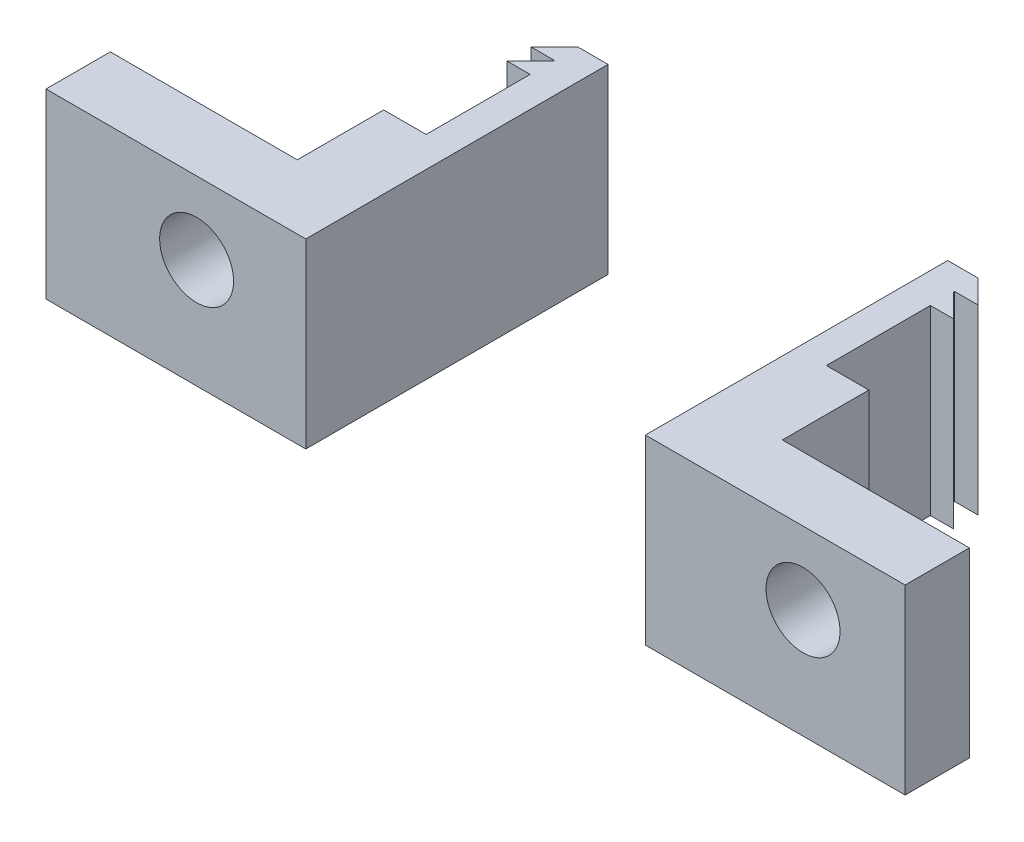
SolidWorks part; units mm, degrees
ref_plane "Front Plane" through (0, 0, 0) normal (0, 0, 1) x (1, 0, 0)
ref_plane "Top Plane" through (0, 0, 0) normal (0, 1, 0) x (1, 0, 0)
ref_plane "Right Plane" through (0, 0, 0) normal (1, 0, 0) x (0, 0, -1)
sketch "Sketch2" plane through (0, 0, 0) normal (0, 1, 0) x (1, 0, 0)
  line L0 (-13.5, 0) -> (6.5, 0)
  line L5 (11.5, -5) -> (11.5, -41)
  line L6 (11.5, -41) -> (31.9173, -41)
  line L7 (31.9173, -41) -> (31.9173, -35.699)
  line L8 (31.9173, -35.699) -> (16.5, -35.699)
  line L9 (16.5, -35.699) -> (16.5, 5)
  line L10 (16.5, 5) -> (-23.5, 5)
  line L11 (-23.5, 5) -> (-23.5, -35.699)
  line L12 (-23.5, -35.699) -> (-38.9173, -35.699)
  line L13 (-38.9173, -35.699) -> (-38.9173, -41)
  line L14 (-38.9173, -41) -> (-18.5, -41)
  line L15 (-18.5, -41) -> (-18.5, -5)
  line L16 (-23.5, -35.699) -> (-23.5, -53.6584) construction
  line L17 (-29.5, -29.038) -> (-29.5, -53.6584) construction
  line L18 (-29.5, -47.6505) -> (-23.5, -47.6505) construction
  line L19 (-3.5, 0) -> (-3.5, -26.0929) construction
  line L20 (-26.5, -47.6505) -> (-26.5, -68.2741) construction
  line L21 (23.5, -24.9282) -> (23.5, -62.6056) construction
  line L22 (20.5, -24.4655) -> (20.5, -49.1581) construction
  line L23 (26.5, -24.4655) -> (26.5, -49.1581) construction
  line L24 (20.5, -44.8687) -> (26.5, -44.8687) construction
  line L25 (23.5, -44.8687) -> (23.5, -42.6651) construction
  line L26 (-18.5, -5) -> (-13.5, 0)
  line L27 (6.5, 0) -> (11.5, -5)
  point P0 (-18.5, 0)
  point P1 (11.5, 0)
  point P23 (-3.5, -23.0301)
  point P34 (23.5, -43.7669)
  dimension "D1" = 30
  dimension "D2" = 5
  dimension "D3" = 5
  dimension "D4" = 46
  dimension "D5" = 6
  dimension "D6" = 50
  dimension "D7" = 6
extrude "Boss-Extrude1" add sketch "Sketch2" along normal blind 15
sketch "Sketch3" plane through (0, 0, 35.699) normal (0, 0, -1) x (-1, 0, 0)
  line L0 (-31.9173, 9) -> (43.2878, 9) construction
  line L1 (-31.9173, 15) -> (-31.9173, 0) construction
  line L2 (-16.5, 15) -> (23.5, 15) construction
  line L3 (-23.5, 15) -> (26.5, 15) construction
  line L4 (23.5, 15) -> (38.9173, 15) construction
  line L6 (-23.5, 15) -> (-23.5, -3.7562) construction
  line L7 (26.5, 15) -> (26.5, -7.565) construction
  line L8 (23.5, 15) -> (23.5, 0) construction
  circle A0 centre (26.5, 9) radius 3.05
  circle A1 centre (-23.5, 9) radius 3.05
  point P11 (1.5, 15)
  dimension "D4" = 6.1
  dimension "D1" = 6
  dimension "D2" = 50
  dimension "D3" = 3
extrude "Cut-Extrude1" cut sketch "Sketch3" against normal blind 15
sketch "Sketch4" plane through (0, 15, 0) normal (0, 1, 0) x (1, 0, 0)
  line L0 (-13.0972, 0) -> (6.5, 0) construction
  line L1 (-13.5, 0) -> (6.5, 0) construction
  line L2 (6.5, 0) -> (11.5, -5) construction
  line L3 (-23.5, -10) -> (18.1067, -10) construction
  line L4 (-23.5, 5) -> (-23.5, -35.699) construction
  line L5 (-23.5, -25.7032) -> (-18.5, -25.7032) construction
  line L6 (-18.5, -41) -> (-18.5, -5) construction
  line L7 (-21, -25.7032) -> (-21, 5) construction
  line L8 (16.5, 5) -> (-23.5, 5) construction
  line L9 (-20, 2.3375) -> (-20, -23.3678) construction
  line L10 (-22, 3.2587) -> (-22, -23.3678) construction
  line L11 (-23.5, -12) -> (-15.7746, -12) construction
  line L12 (-20, -10) -> (-22, -12)
  line L13 (-22, -12) -> (-20, -12) construction
  line L14 (-20.075, -12.075) -> (-22, -14)
  line L15 (-20, -16.075) -> (-18.4226, -16.075)
  line L16 (-20.075, -14.075) -> (-22, -16)
  line L17 (-22, -20.075) -> (-23.6463, -20.075)
  line L18 (-20.075, -16.075) -> (-22, -18)
  line L19 (-21.925, -18) -> (-20, -18)
  line L20 (-20.075, -18.075) -> (-22, -20)
  line L21 (-21.925, -20) -> (-20, -20)
  line L22 (-20, -20) -> (-20, -28.575)
  line L23 (-22, -12.075) -> (-20.075, -12.075)
  line L24 (-18.5, -19.4434) -> (-18.5, -20.4817) construction
  line L25 (-22, -14.075) -> (-20.075, -14.075)
  line L26 (-20, -28.575) -> (-23.5, -28.575)
  line L27 (-22, -16.075) -> (-20.075, -16.075)
  line L28 (-20, -16.075) -> (-21.925, -18)
  line L29 (-22, -18.075) -> (-20.075, -18.075)
  line L30 (-20, -18.075) -> (-21.925, -20)
  line L31 (-3.5, 5) -> (-3.5, -28.6388) construction
  line L32 (13, -16.075) -> (11.4226, -16.075)
  line L33 (-20, -10) -> (-18.5, -10)
  line L34 (-22, -12) -> (-22, -12.075)
  line L35 (-22, -14) -> (-22, -14.075)
  line L36 (-22, -16) -> (-22, -16.075)
  line L37 (-22, -18) -> (-22, -18.075)
  line L38 (-22, -20) -> (-22, -20.075)
  line L39 (-20, -18) -> (-20, -18.075)
  line L40 (13, -16.075) -> (14.925, -18)
  line L41 (14.925, -18) -> (13, -18)
  line L42 (13, -18) -> (13, -18.075)
  line L43 (13, -18.075) -> (14.925, -20)
  line L44 (-21.925, -16) -> (-21, -16) [skipped]
  line L45 (-21.925, -14) -> (-21, -14) [skipped]
  line L46 (14.925, -20) -> (13, -20)
  line L47 (13, -20) -> (13, -28.575)
  line L48 (13, -28.575) -> (16.5, -28.575)
  line L49 (11.4226, -16.075) -> (-18.4226, -16.075)
  line L50 (-23.5, -28.575) -> (-33.2508, -28.575)
  line L51 (-33.2508, -28.575) -> (-33.2508, 6.3001)
  line L52 (-33.2508, 6.3001) -> (24.863, 6.3001)
  line L53 (24.863, 6.3001) -> (24.863, -28.575)
  line L54 (24.863, -28.575) -> (16.5, -28.575)
  dimension "D1" = 10
  dimension "D2" = 1
  dimension "D3" = 1
  dimension "D4" = 2
  dimension "D6" = 8.575
  dimension "D5" = 5
extrude "Cut-Extrude2" cut sketch "Sketch4" against normal through all
sketch "Sketch5" plane through (0, 0, 35.699) normal (0, 0, -1) x (-1, 0, 0)
  circle A0 centre (26.5, 9) radius 6
  dimension "D1" = 12
extrude "Cut-Extrude3" cut sketch "Sketch5" along normal blind 10
sketch "Sketch6" plane through (-18.5, 0, 0) normal (1, 0, 0) x (0, 0, -1)
  line L1 (-41, 0) -> (-16.075, 0)
  line L2 (-41, 0) -> (-41, 15)
  line L3 (-41, 15) -> (-16.075, 15)
  line L4 (-16.075, 0) -> (-16.075, 15)
extrude "Boss-Extrude2" add sketch "Sketch6" along normal blind 1
sketch "Sketch7" plane through (11.5, 0, 0) normal (-1, 0, 0) x (0, 0, 1)
  line L1 (41, 0) -> (16.075, 0)
  line L2 (41, 0) -> (41, 15)
  line L3 (41, 15) -> (16.075, 15)
  line L4 (16.075, 0) -> (16.075, 15)
extrude "Boss-Extrude3" add sketch "Sketch7" along normal blind 1
